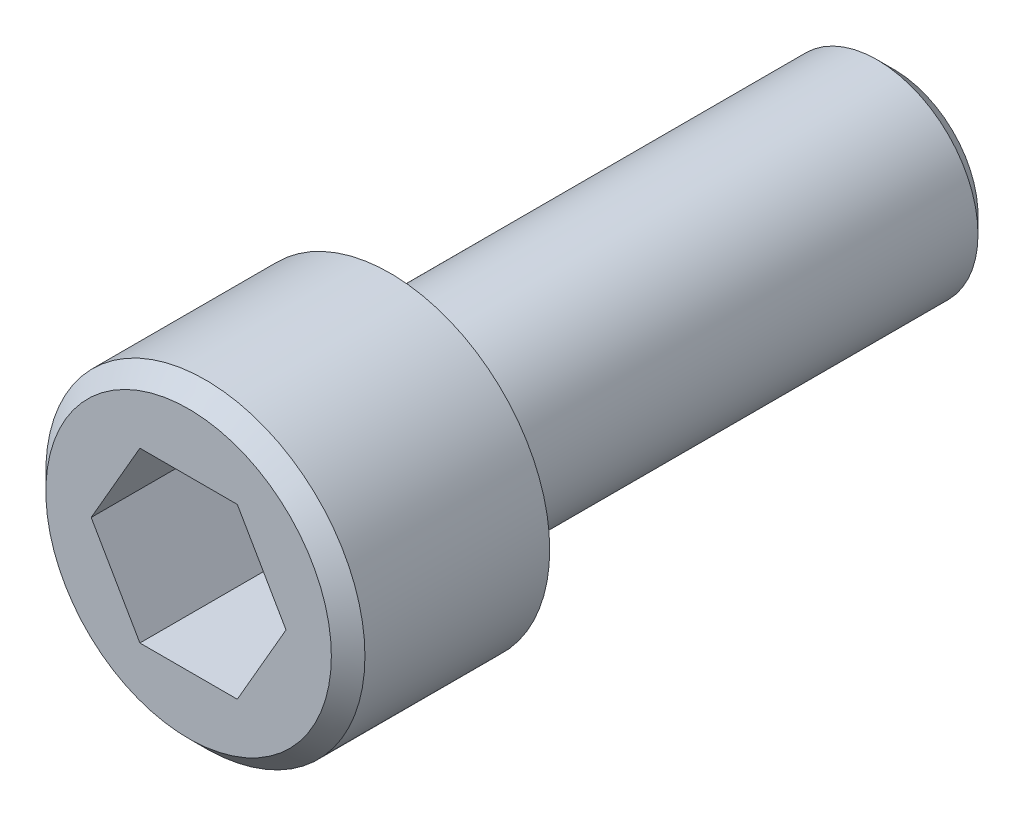
SolidWorks part; units mm, degrees
ref_plane "Alzado" through (0, 0, 0) normal (0, 0, 1) x (1, 0, 0)
ref_plane "Planta" through (0, 0, 0) normal (0, 1, 0) x (1, 0, 0)
ref_plane "Vista lateral" through (0, 0, 0) normal (1, 0, 0) x (0, 0, -1)
sketch "Croquis1" plane through (0, 0, 0) normal (0, 0, 1) x (1, 0, 0)
  circle A0 centre (0, 0) radius 9.5
  dimension "D1" = 19
extrude "Saliente-Extruir1" add sketch "Croquis1" along normal blind 12
sketch "Croquis2" plane through (0, 0, 0) normal (0, 0, -1) x (-1, 0, 0)
  circle A0 centre (0, 0) radius 6
  dimension "D1" = 12
extrude "Saliente-Extruir2" add sketch "Croquis2" along normal blind 30
chamfer "Chaflán1" distance 1 angle 45 2 edges at (9.5, 0, 12) (-6, 0, -30)
sketch "Croquis3" plane through (0, 0, 12) normal (0, 0, 1) x (1, 0, 0)
  line L1 (5.8, 0) -> (2.9, 5.0229)
  line L2 (2.9, 5.0229) -> (-2.9, 5.0229)
  line L3 (-2.9, 5.0229) -> (-5.8, 0)
  line L4 (-5.8, 0) -> (-2.9, -5.0229)
  line L5 (-2.9, -5.0229) -> (2.9, -5.0229)
  line L6 (2.9, -5.0229) -> (5.8, 0)
  circle A0 centre (0, 0) radius 5.0229 construction
  dimension "D1" = 11.6
extrude "Cortar-Extruir1" cut sketch "Croquis3" against normal blind 8
